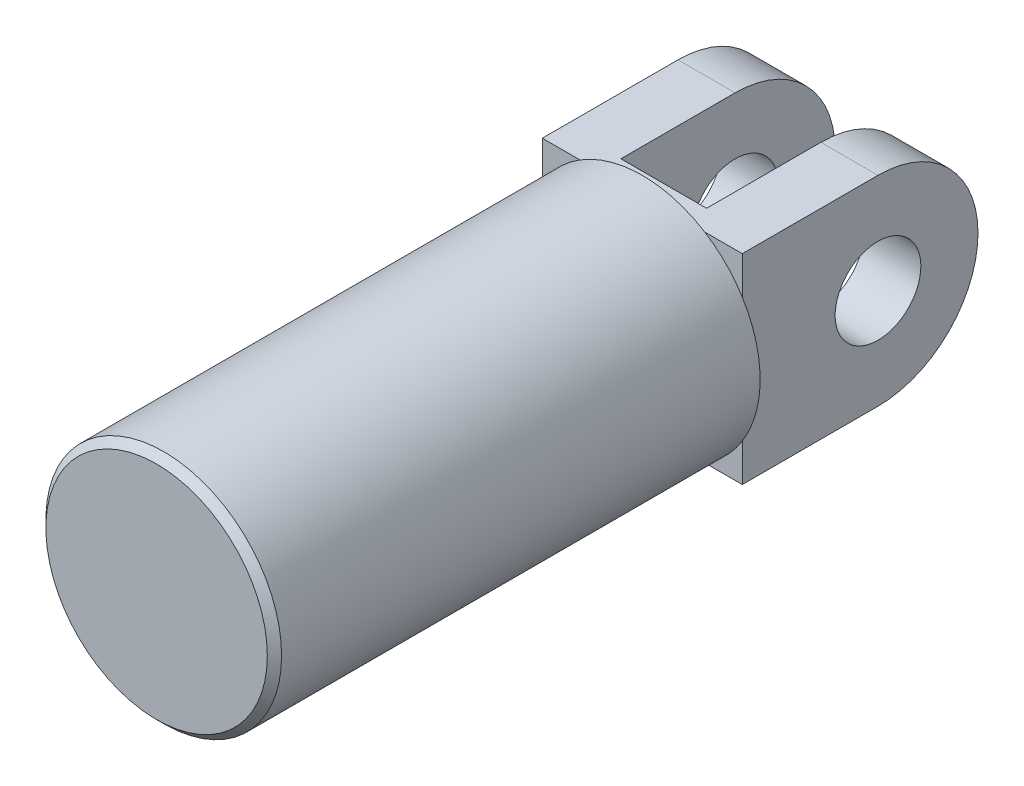
SolidWorks part; units mm, degrees
ref_plane "前基準面" through (0, 0, 0) normal (0, 0, 1) x (1, 0, 0)
ref_plane "上基準面" through (0, 0, 0) normal (0, 1, 0) x (1, 0, 0)
ref_plane "右基準面" through (0, 0, 0) normal (1, 0, 0) x (0, 0, -1)
sketch "草圖1" plane through (0, 0, 0) normal (0, 0, 1) x (1, 0, 0)
  circle A0 centre (0, 0) radius 16.5
  dimension "D1" = 33
extrude "伸長1" add sketch "草圖1" along normal blind 68
chamfer "導角1" distance 1 angle 45 1 edges at (16.5, 0, 68)
sketch "草圖3" plane through (0, 0, 0) normal (1, 0, 0) x (0, 0, -1)
  line L0 (0, 14) -> (19, 14)
  line L1 (0, -16.5) -> (0, 16.5) construction
  line L2 (19, -14) -> (0, -14)
  line L3 (0, -14) -> (0, 14)
  arc A0 (19, 14) -> (19, -14) centre (19, 0) cw
  circle A1 centre (19, 0) radius 6
  dimension "D1" = 14
  dimension "D2" = 12
  dimension "D3" = 19
extrude "伸長2" add sketch "草圖3" along normal mid plane 28
sketch "草圖4" plane through (0, 0, 0) normal (1, 0, 0) x (0, 0, -1)
  line L0 (3, 14) -> (3, -14)
  line L1 (0, 14) -> (0, 8.7321) construction
  line L5 (0, 14) -> (0, 8.7321)
  line L6 (0, 8.7321) -> (0, -8.7321)
  line L7 (0, -8.7321) -> (0, -14)
  line L8 (0, -14) -> (19, -14)
  line L9 (19, 14) -> (0, 14)
  line L13 (3, -14) -> (19, -14)
  line L14 (19, 14) -> (3, 14)
  arc A1 (19, -14) -> (19, 14) centre (19, 0) ccw
  arc A2 (19, -14) -> (19, 14) centre (19, 0) ccw
  dimension "D2" = 3
  dimension "D1" = 0
extrude "伸長3" cut sketch "草圖4" against normal mid plane 12
